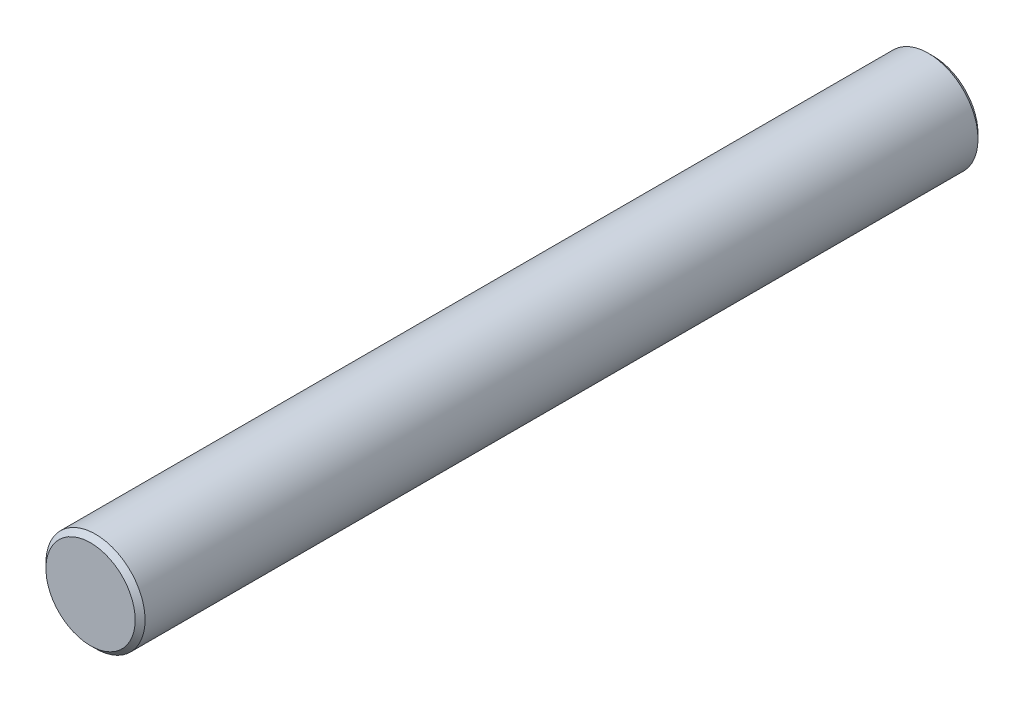
SolidWorks part; units mm, degrees
ref_plane "前视基准面" through (0, 0, 0) normal (0, 0, 1) x (1, 0, 0)
ref_plane "上视基准面" through (0, 0, 0) normal (0, 1, 0) x (1, 0, 0)
ref_plane "右视基准面" through (0, 0, 0) normal (1, 0, 0) x (0, 0, -1)
sketch "草图1" plane through (0, 0, 0) normal (0, 0, 1) x (1, 0, 0)
  circle A0 centre (0, 0) radius 10
extrude "拉伸1" add sketch "草图1" along normal blind 170
chamfer "倒角1" distance 1 angle 45 2 edges at (10, 0, 0) (10, 0, 170)
